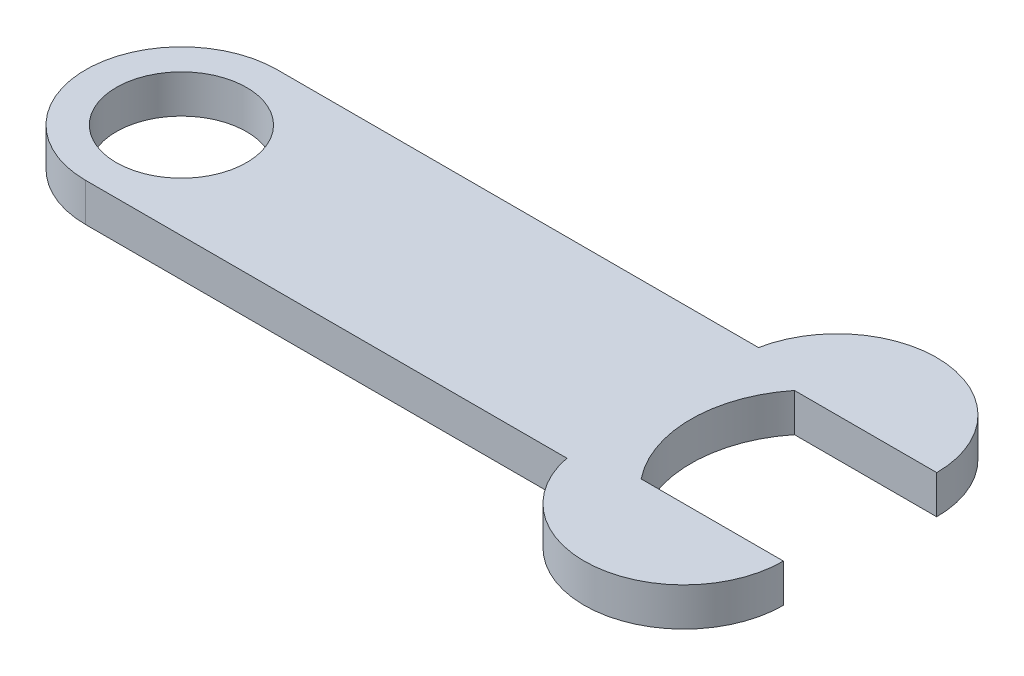
SolidWorks part; units mm, degrees
ref_plane "Front Plane" through (0, 0, 0) normal (0, 0, 1) x (1, 0, 0)
ref_plane "Top Plane" through (0, 0, 0) normal (0, 1, 0) x (1, 0, 0)
ref_plane "Right Plane" through (0, 0, 0) normal (1, 0, 0) x (0, 0, -1)
sketch "Sketch1" plane through (0, 0, 0) normal (0, 1, 0) x (1, 0, 0)
  line L0 (0, 0) -> (-164.9, 0) construction
  line L3 (-13.8, 41.0782) -> (-13.8, -39.1129) construction
  line L4 (-24.934, 20) -> (12.2, 20)
  line L6 (-24.934, -20) -> (12.2, -20)
  line L8 (-24.934, 20) -> (12.2, -9.7858) construction
  line L9 (-24.934, -20) -> (12.2, 9.7858) construction
  line L10 (12.2, 25) -> (12.2, -25) construction
  line L11 (-39.3147, -25) -> (-164.9, -25)
  line L12 (-39.3147, 25) -> (-164.9, 25)
  arc A1 (-164.9, 25) -> (-164.9, -25) centre (-164.9, 0) ccw
  circle A2 centre (-164.9, 0) radius 17
  arc A3 (-24.934, 20) -> (-24.934, -20) centre (0.046, 0) ccw
  arc A5 (-39.3147, -25) -> (12.2, -20) centre (-13.8, -20) ccw
  arc A7 (12.2, 20) -> (-39.3147, 25) centre (-13.8, 20) ccw
  point P3 (-82.45, 0)
  dimension "D2" = 25
  dimension "D3" = 34
  dimension "D4" = 32
  dimension "D1" = 164.9
  dimension "D5" = 40
  dimension "D6" = 13.8
  dimension "D7" = 26
  dimension "D8" = 26
extrude "Boss-Extrude1" add sketch "Sketch1" along normal blind 10
